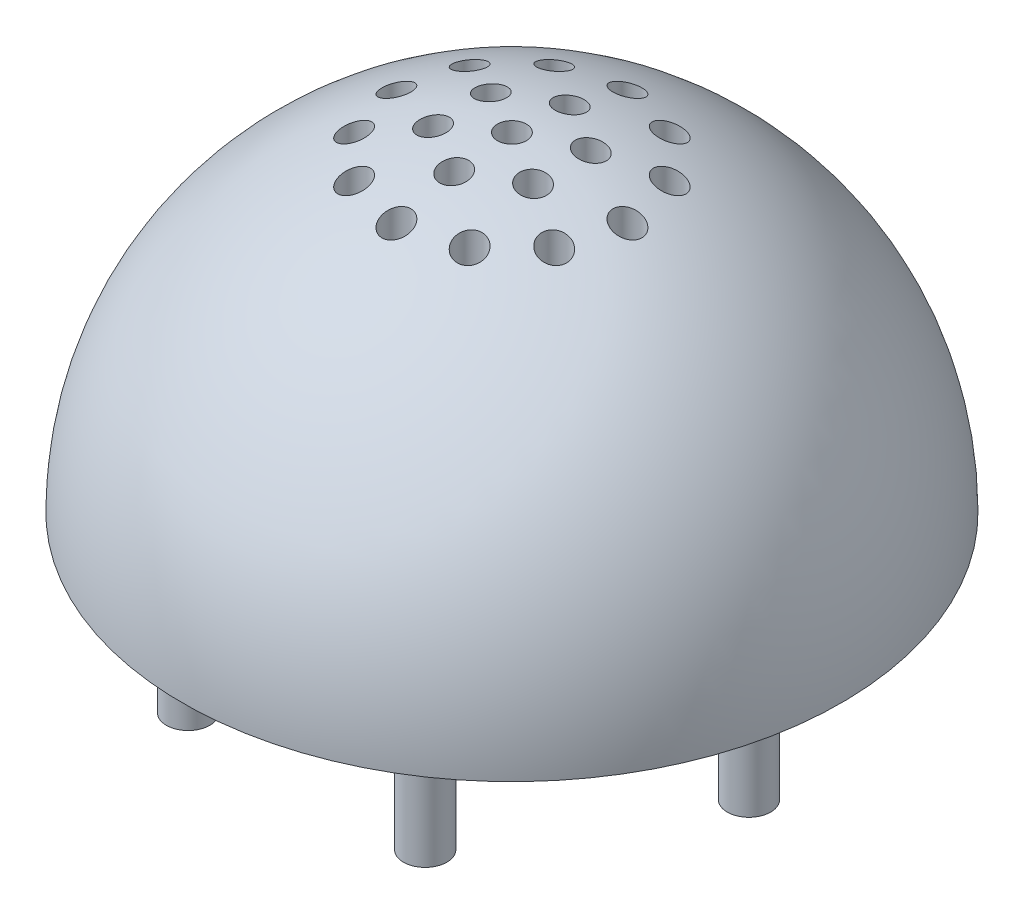
SolidWorks part; units mm, degrees
ref_plane "Piano frontale" through (0, 0, 0) normal (0, 0, 1) x (1, 0, 0)
ref_plane "Piano superiore" through (0, 0, 0) normal (0, 1, 0) x (1, 0, 0)
ref_plane "Piano destro" through (0, 0, 0) normal (1, 0, 0) x (0, 0, -1)
sketch "Schizzo1" plane through (0, 0, 0) normal (0, 1, 0) x (1, 0, 0)
  circle A0 centre (0, 0) radius 5
  circle A1 centre (0, 0) radius 9
  dimension "D1" = 10
  dimension "D2" = 18
extrude "Estrusione-Estrusione2" add sketch "Schizzo1" along normal blind 7 contours A1
sketch "Schizzo4" plane through (0, 0, 0) normal (0, 0, 1) x (1, 0, 0)
  line L0 (0, 0) -> (0, 16.8551) construction
  line L1 (11.4018, 0) -> (0, 0)
  line L2 (0, 0) -> (0, 11.4018)
  arc A0 (11.4018, 0) -> (0, 11.4018) centre (0, 0) ccw
revolve "Rivoluzione3" add sketch "Schizzo4" angle 360 about L0
sketch "Schizzo5" plane through (0, 0, 0) normal (0, -1, 0) x (1, 0, 0)
  circle A0 centre (0, 0) radius 5
  dimension "D1" = 10
extrude "Taglio-Estrusione1" cut sketch "Schizzo5" against normal blind 9
sketch "Schizzo6" plane through (0, 9, 0) normal (0, -1, 0) x (1, 0, 0)
  line L0 (0, -3.9962) -> (0, 0) construction
  circle A0 centre (0, -3.9962) radius 0.5
  circle A1 centre (0, 0) radius 0.5
  circle A2 centre (0, -1.9981) radius 0.5
  circle A3 centre (-1.7304, -0.999) radius 0.5
  circle A4 centre (-1.7304, 0.999) radius 0.5
  circle A5 centre (0, 1.9981) radius 0.5
  circle A6 centre (1.7304, 0.999) radius 0.5
  circle A7 centre (1.7304, -0.999) radius 0.5
  circle A8 centre (-1.9981, -3.4608) radius 0.5
  circle A9 centre (-3.4608, -1.9981) radius 0.5
  circle A10 centre (-3.9962, 0) radius 0.5
  circle A11 centre (-3.4608, 1.9981) radius 0.5
  circle A12 centre (-1.9981, 3.4608) radius 0.5
  circle A13 centre (0, 3.9962) radius 0.5
  circle A14 centre (1.9981, 3.4608) radius 0.5
  circle A15 centre (3.4608, 1.9981) radius 0.5
  circle A16 centre (3.9962, 0) radius 0.5
  circle A17 centre (3.4608, -1.9981) radius 0.5
  circle A18 centre (1.9981, -3.4608) radius 0.5
  point P20 (0, 0)
  point P43 (0, 0)
  dimension "D1" = 1
  dimension "D2" = 1
  dimension "D3" = 1
  dimension "D4" = 6
  dimension "D5" = 12
extrude "Taglio-Estrusione2" cut sketch "Schizzo6" against normal blind 9
sketch "Schizzo7" plane through (0, 0, 0) normal (0, -1, 0) x (1, 0, 0)
  line L0 (5, 0) -> (11.4018, 0) construction
  circle A0 centre (0, 0) radius 5 construction
  circle A1 centre (0, 0) radius 5 construction
  circle A2 centre (0, 0) radius 11.4018 construction
  circle A3 centre (8.2009, 0) radius 0.75
  circle A4 centre (4.1004, -7.1022) radius 0.75
  circle A5 centre (-4.1004, -7.1022) radius 0.75
  circle A6 centre (-8.2009, 0) radius 0.75
  circle A7 centre (-4.1004, 7.1022) radius 0.75
  circle A8 centre (4.1004, 7.1022) radius 0.75
  point P25 (0, 0)
  dimension "D1" = 1.5
  dimension "D2" = 6
extrude "Estrusione-Estrusione3" add sketch "Schizzo7" along normal blind 4.5
